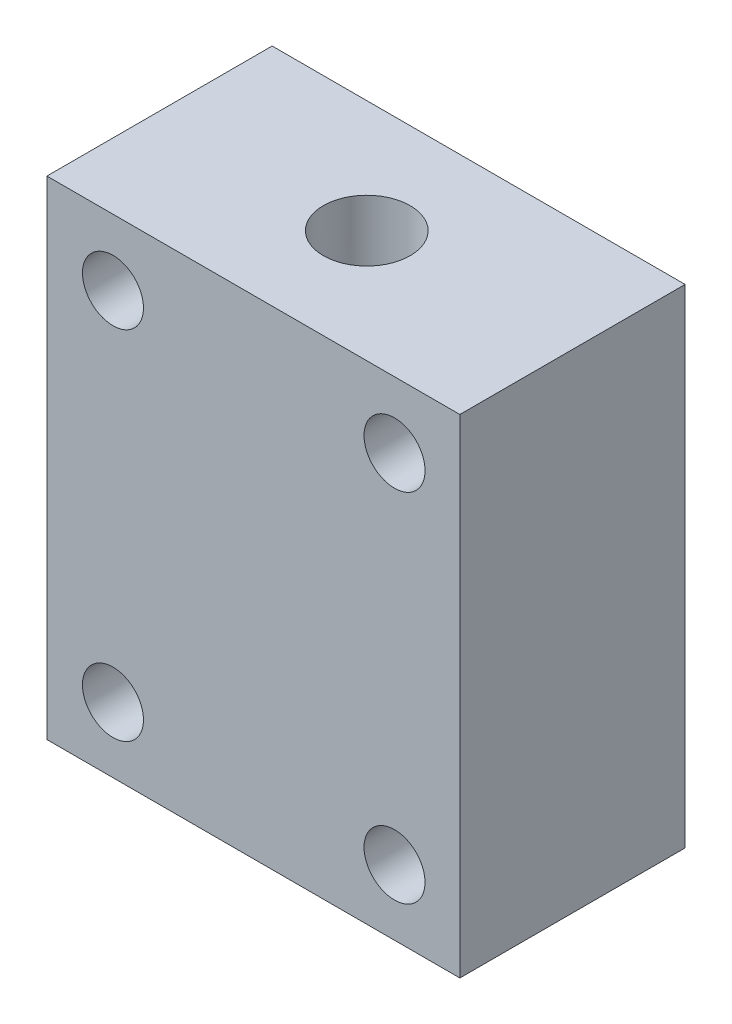
SolidWorks part; units mm, degrees
ref_plane "Front Plane" through (0, 0, 0) normal (1, 0, 0) x (0, 1, 0)
ref_plane "Top Plane" through (0, 0, 0) normal (0, 0, 1) x (0, 1, 0)
ref_plane "Right Plane" through (0, 0, 0) normal (0, 1, 0) x (-1, 0, 0)
sketch "Sketch1" plane through (0, 0, 0) normal (0, 0, 1) x (0, 1, 0)
  line L1 (-41.275, -34.925) -> (41.275, -34.925)
  line L2 (-41.275, -34.925) -> (-41.275, 34.925)
  line L3 (-41.275, 34.925) -> (41.275, 34.925)
  line L4 (41.275, -34.925) -> (41.275, 34.925)
  line L5 (-41.275, -34.925) -> (41.275, 34.925) construction
  line L6 (-41.275, 34.925) -> (41.275, -34.925) construction
  point P0 (0, 0)
  dimension "D1" = 41.275
  dimension "D2" = 34.925
extrude "Boss-Extrude1" add sketch "Sketch1" along normal mid plane 38.1
hole_wizard "3/8 Clearance Hole1" positions "Sketch3" profile "Sketch2" hole size "3/8" standard "ANSI Inch"
sketch "Sketch3" plane through (0, 0, -19.05) normal (0, 0, -1) x (-1, 0, 0)
  line L0 (-23.876, -30.226) -> (23.749, -30.226) construction
  line L1 (23.749, -30.226) -> (23.749, 30.099) construction
  line L2 (23.749, 30.099) -> (-23.876, 30.099) construction
  line L3 (-23.876, 30.099) -> (-23.876, -30.226) construction
  line L4 (-34.925, -41.275) -> (-34.925, 41.275) construction
  line L5 (-34.925, 41.275) -> (34.925, 41.275) construction
  point P0 (-23.876, -30.226)
  point P1 (-23.876, 30.099)
  point P3 (23.749, -30.226)
  point P5 (23.749, 30.099)
  dimension "D1" = 11.049
  dimension "D2" = 58.674
  dimension "D3" = 11.176
  dimension "D4" = 71.501
sketch "Sketch2" plane through (23.876, -30.226, -19.05) normal (1, 0, 0) x (0, 1, 0)
  line L0 (0, 0) -> (0, 41.2001)
  line L1 (0, 41.2001) -> (5.1594, 38.1)
  line L2 (5.1594, 38.1) -> (5.1594, 0)
  line L5 (5.1594, 0) -> (0, 0)
  line L10 (0, 41.2001) -> (-5.1594, 38.1) construction
  line L11 (0, -6.35) -> (0, 107.95) construction
  dimension "Hole Dia." = 10.3187
  dimension "Hole Depth" = 38.1
  dimension "Drill Angle" = 118
sketch "Sketch4" plane through (0, 0, 0) normal (0, 0, 1) x (0, 1, 0)
  circle A0 centre (-17.653, -0.127) radius 7.3422
  circle A1 centre (17.399, -0.127) radius 7.3422
  point P4 (0, 0)
  dimension "D1" = 14.6844
  dimension "D2" = 14.6844
  dimension "D3" = 35.052
  dimension "D4" = 17.653
  dimension "D5" = 0.127
extrude "Cut-Extrude2" cut sketch "Sketch4" along normal blind 28.448 from offset 19.05
sketch "Sketch5" plane through (0, 0, 0) normal (0, 0, 1) x (0, 1, 0)
  circle A0 centre (-17.653, -0.127) radius 12.7254
  circle A1 centre (17.399, -0.127) radius 12.7254
  point P4 (0, 0)
  dimension "D1" = 25.4508
  dimension "D2" = 25.4508
  dimension "D3" = 35.052
  dimension "D4" = 17.653
  dimension "D5" = 0.127
extrude "Cut-Extrude4" cut sketch "Sketch5" along normal blind 2.8194 from offset 19.05
sketch "Sketch6" plane through (0, 0, 0) normal (0, 1, 0) x (-1, 0, 0)
  circle A0 centre (-0.127, 0) radius 7.3422
  point P2 (0, 0)
  dimension "D1" = 14.6844
  dimension "D2" = 0.127
extrude "Cut-Extrude6" cut sketch "Sketch6" against normal blind 60.452 from offset 41.275
